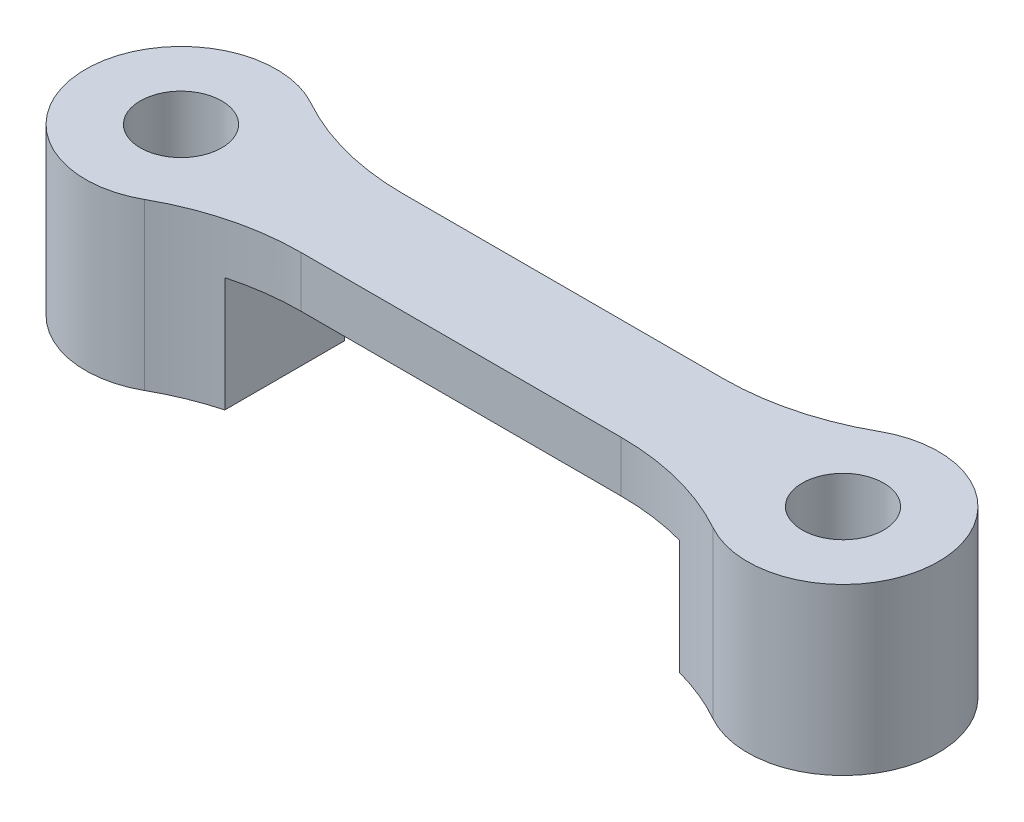
SolidWorks part; units mm, degrees
ref_plane "Front Plane" through (0, 0, 0) normal (0, 0, 1) x (1, 0, 0)
ref_plane "Top Plane" through (0, 0, 0) normal (0, 1, 0) x (1, 0, 0)
ref_plane "Right Plane" through (0, 0, 0) normal (1, 0, 0) x (0, 0, -1)
sketch "Sketch1" plane through (0, 0, 0) normal (0, 1, 0) x (1, 0, 0)
  line L0 (13, 0) -> (-13, 0) construction
  line L1 (-9.8279, 2) -> (9.8279, 2)
  line L2 (-9.8279, -2) -> (9.8279, -2)
  circle A0 centre (-13, 0) radius 1.6
  circle A1 centre (13, 0) radius 1.6
  circle A2 centre (-13, 0) radius 3.75
  circle A3 centre (13, 0) radius 3.75
  point P4 (0, 0)
  dimension "D2" = 3.2
  dimension "D3" = 7.5
  dimension "D1" = 26
  dimension "D4" = 4
extrude "Boss-Extrude1" add sketch "Sketch1" along normal blind 6.5
fillet "Fillet1" radius 10 4 edges at (9.8279, 3.25, 2) (9.8279, 3.25, -2) (-9.8279, 3.25, -2) (-9.8279, 3.25, 2)
sketch "Sketch2" plane through (0, 0, 0) normal (0, -1, 0) x (-1, 0, 0)
  line L1 (-8.925, 2.3542) -> (8.925, 2.3542)
  line L2 (-8.925, 2.3542) -> (-8.925, -2.3542)
  line L3 (-8.925, -2.3542) -> (8.925, -2.3542)
  line L4 (8.925, 2.3542) -> (8.925, -2.3542)
  line L5 (-8.925, 2.3542) -> (8.925, -2.3542) construction
  line L6 (-8.925, -2.3542) -> (8.925, 2.3542) construction
  arc A2 (11.1692, -3.2727) -> (6.2871, -2) centre (6.2871, -12) ccw construction
  point P0 (0, 0)
  dimension "D1" = 17.85
extrude "Cut-Extrude1" cut sketch "Sketch2" against normal blind 4.5
chamfer "Chamfer1" [suppressed] distance 1.6 angle 45
